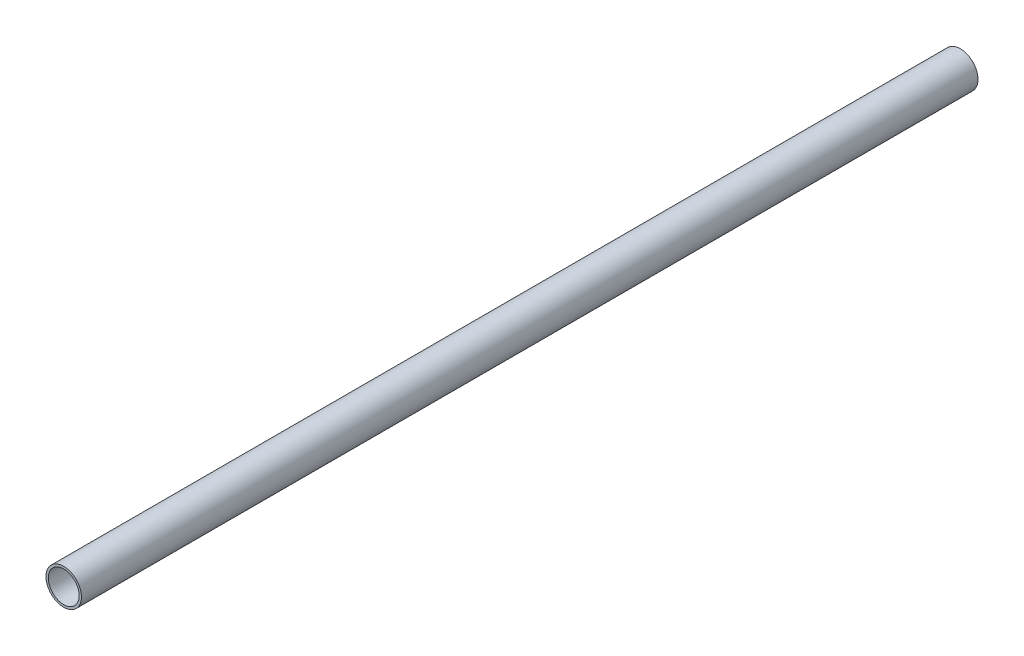
SolidWorks part; units mm, degrees
ref_plane "Front Plane" through (0, 0, 0) normal (0, 0, 1) x (1, 0, 0)
ref_plane "Top Plane" through (0, 0, 0) normal (0, 1, 0) x (1, 0, 0)
ref_plane "Right Plane" through (0, 0, 0) normal (1, 0, 0) x (0, 0, -1)
sketch "Sketch1" plane through (0, 0, 0) normal (0, 0, 1) x (1, 0, 0)
  circle A0 centre (0, 0) radius 30.1625
  circle A1 centre (0, 0) radius 26.2509
  dimension "D1" = 60.325
  dimension "D2" = 3.9116
extrude "Boss-Extrude1" add sketch "Sketch1" along normal blind 1524
